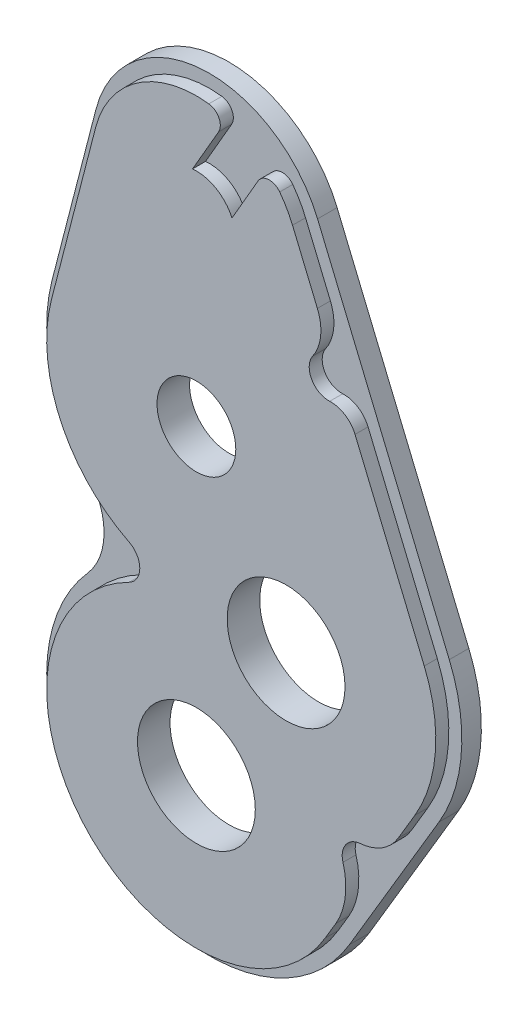
SolidWorks part; units mm, degrees
ref_plane "Front Plane" through (0, 0, 0) normal (0, 0, 1) x (1, 0, 0)
ref_plane "Top Plane" through (0, 0, 0) normal (0, 1, 0) x (1, 0, 0)
ref_plane "Right Plane" through (0, 0, 0) normal (1, 0, 0) x (0, 0, -1)
sketch "Sketch1" plane through (0, 0, 0) normal (0, 0, 1) x (1, 0, 0)
  line L0 (0, 0) -> (0, -74.44) construction
  line L1 (0, -28) -> (13.7779, -51.22) construction
  line L2 (13.7779, -51.22) -> (0, -74.44) construction
  line L3 (-17.4284, 4.5) -> (-24.2061, -21.75)
  line L4 (-46.6534, -39) -> (66.3979, -39) construction
  line L5 (35.2779, -63.9774) -> (21.5, -87.1974)
  line L6 (36.8516, -41.5967) -> (16.613, 6.9288)
  line L7 (-25, -74.44) -> (-25, -28) construction
  line L8 (38.7779, 1.4363) -> (38.7779, -91.7608) construction
  line L9 (-18, 7.4714) -> (-18, -38.8167) construction
  circle A0 centre (0, 0) radius 9 construction
  circle A1 centre (0, -28) radius 21 construction
  circle A2 centre (0, -74.44) radius 21 construction
  circle A3 centre (13.7779, -51.22) radius 21 construction
  circle A4 centre (0, 0) radius 9 construction
  arc A12 (-17.4284, 4.5) -> (16.613, 6.9288) centre (0, 0) ccw construction
  arc A13 (-18.706, -57.8543) -> (21.5, -87.1974) centre (0, -74.44) ccw
  arc A14 (35.2779, -63.9774) -> (36.8516, -41.5967) centre (13.7779, -51.22) ccw
  circle A18 centre (0, 0) radius 4.5 construction
  arc A19 (16.613, 6.9288) -> (-17.4284, 4.5) centre (0, 0) ccw construction
  arc A20 (16.613, 6.9288) -> (-17.4284, 4.5) centre (0, 0) ccw
  arc A22 (-24.2061, -21.75) -> (-18.706, -44.5857) centre (0, -28) ccw
  circle A23 centre (0, -28) radius 6.05
  circle A24 centre (13.7779, -51.22) radius 9.05
  circle A25 centre (0, -74.44) radius 9.05
  arc A32 (-18.706, -57.8543) -> (-18.706, -44.5857) centre (-26.1884, -51.22) ccw
  point P13 (0, -2.75)
  point P48 (0, 0)
  dimension "D1" = 18
  dimension "D4" = 12.1
  dimension "D5" = 18.1
  dimension "D6" = 50
  dimension "D7" = 50
  dimension "D8" = 18.1
  dimension "D2" = 28
  dimension "D3" = 74.44
extrude "Boss-Extrude1" add sketch "Sketch1" along normal blind 5
sketch "Sketch2" plane through (0, 0, 5) normal (0, 0, 1) x (1, 0, 0)
  line L1 (9.4683, 9.3996) -> (5.4678, 2.4705)
  line L2 (3.4061, 12.8996) -> (-0.5944, 5.9705)
  line L3 (16.613, 6.9288) -> (36.8516, -41.5967)
  line L4 (16.613, 6.9288) -> (36.8516, -41.5967)
  line L5 (35.2779, -63.9774) -> (21.5, -87.1974)
  line L6 (35.2779, -63.9774) -> (21.5, -87.1974)
  line L7 (-24.2061, -21.75) -> (-17.4284, 4.5)
  line L8 (-24.2061, -21.75) -> (-17.4284, 4.5)
  line L9 (14.7671, 6.1589) -> (18.5855, -2.9963)
  line L10 (33.5579, -62.9568) -> (31.009, -67.2525)
  line L11 (-22.2697, -22.25) -> (-15.4919, 4)
  line L12 (24.3694, -16.8643) -> (35.0057, -42.3665)
  line L13 (14.7671, 6.1589) -> (35.0057, -42.3665) construction
  line L14 (21.416, -83.4195) -> (19.78, -86.1768)
  line L15 (33.5579, -62.9568) -> (19.78, -86.1768) construction
  arc A0 (-0.5944, 5.9705) -> (5.4678, 2.4705) centre (0, 0) cw
  arc A1 (3.4061, 12.8996) -> (1.9132, 15.8852) centre (1.6741, 13.8996) ccw
  arc A2 (1.9132, 15.8852) -> (-15.4919, 4) centre (0, 0) ccw
  arc A3 (14.7671, 6.1589) -> (-15.4919, 4) centre (0, 0) ccw construction
  arc A4 (12.8004, 9.5995) -> (9.4683, 9.3996) centre (11.2003, 8.3996) ccw
  arc A5 (35.2779, -63.9774) -> (36.8516, -41.5967) centre (13.7779, -51.22) ccw
  arc A6 (35.2779, -63.9774) -> (36.8516, -41.5967) centre (13.7779, -51.22) ccw
  arc A7 (-18.706, -57.8543) -> (21.5, -87.1974) centre (0, -74.44) ccw
  arc A8 (-18.706, -57.8543) -> (21.5, -87.1974) centre (0, -74.44) ccw
  arc A9 (-18.706, -57.8543) -> (-18.706, -44.5857) centre (-26.1884, -51.22) ccw
  arc A11 (-24.2061, -21.75) -> (-18.706, -44.5857) centre (0, -28) ccw
  arc A12 (-24.2061, -21.75) -> (-18.706, -44.5857) centre (0, -28) ccw
  arc A13 (16.613, 6.9288) -> (-17.4284, 4.5) centre (0, 0) ccw
  arc A14 (16.613, 6.9288) -> (-17.4284, 4.5) centre (0, 0) ccw
  arc A15 (33.5579, -62.9568) -> (35.0057, -42.3665) centre (13.7779, -51.22) ccw
  arc A16 (-10.3478, -53.8992) -> (19.78, -86.1768) centre (0, -74.44) ccw
  arc A18 (-22.2697, -22.25) -> (-10.3478, -48.5408) centre (0, -28) ccw
  arc A19 (14.7671, 6.1589) -> (12.8004, 9.5995) centre (0, 0) ccw
  arc A20 (-22.2697, -22.25) -> (-17.4144, -43.0246) centre (0, -28) ccw construction
  arc A21 (-17.4144, -59.4154) -> (19.78, -86.1768) centre (0, -74.44) ccw construction
  arc A22 (-10.3478, -53.8992) -> (-10.3478, -48.5408) centre (-11.6975, -51.22) ccw
  circle A23 centre (-11.6975, -51.22) radius 3 construction
  arc A24 (-18.706, -57.8543) -> (-18.706, -44.5857) centre (-26.1884, -51.22) ccw
  arc A25 (-18.706, -57.8543) -> (-18.706, -44.5857) centre (-22.4188, -51.22) ccw construction
  arc A26 (-17.4144, -59.4154) -> (-17.4144, -43.0246) centre (-22.4188, -51.22) ccw construction
  circle A27 centre (-26.1884, -51.22) radius 10 construction
  circle A28 centre (-11.6975, -51.22) radius 1.25 construction
  circle A29 centre (20.3259, -11.4129) radius 1.25 construction
  arc A30 (17.8656, -9.6963) -> (20.4767, -14.4091) centre (20.3259, -11.4129) ccw
  arc A31 (17.8656, -9.6963) -> (18.5855, -2.9963) centre (12.1249, -5.6908) ccw
  arc A32 (24.3694, -16.8643) -> (20.4767, -14.4091) centre (20.6777, -18.4041) ccw
  circle A33 centre (25.3976, -73.8917) radius 1.25 construction
  arc A34 (25.158, -70.9013) -> (22.5173, -74.7306) centre (25.3976, -73.8917) ccw
  arc A35 (25.158, -70.9013) -> (31.009, -67.2525) centre (24.559, -63.4253) ccw
  arc A36 (21.416, -83.4195) -> (22.5173, -74.7306) centre (11.956, -77.8063) ccw
  dimension "D2" = 6
  dimension "D3" = 14.4909
  dimension "D1" = 2
extrude "Cut-Extrude1" cut sketch "Sketch2" against normal blind 2
sketch "Sketch3" plane through (0, 0, 3) normal (0, 0, 1) x (1, 0, 0)
  circle A0 centre (20.3259, -11.4129) radius 1.25
  circle A1 centre (-11.6975, -51.22) radius 1.25
  circle A2 centre (25.3976, -73.8917) radius 1.25
